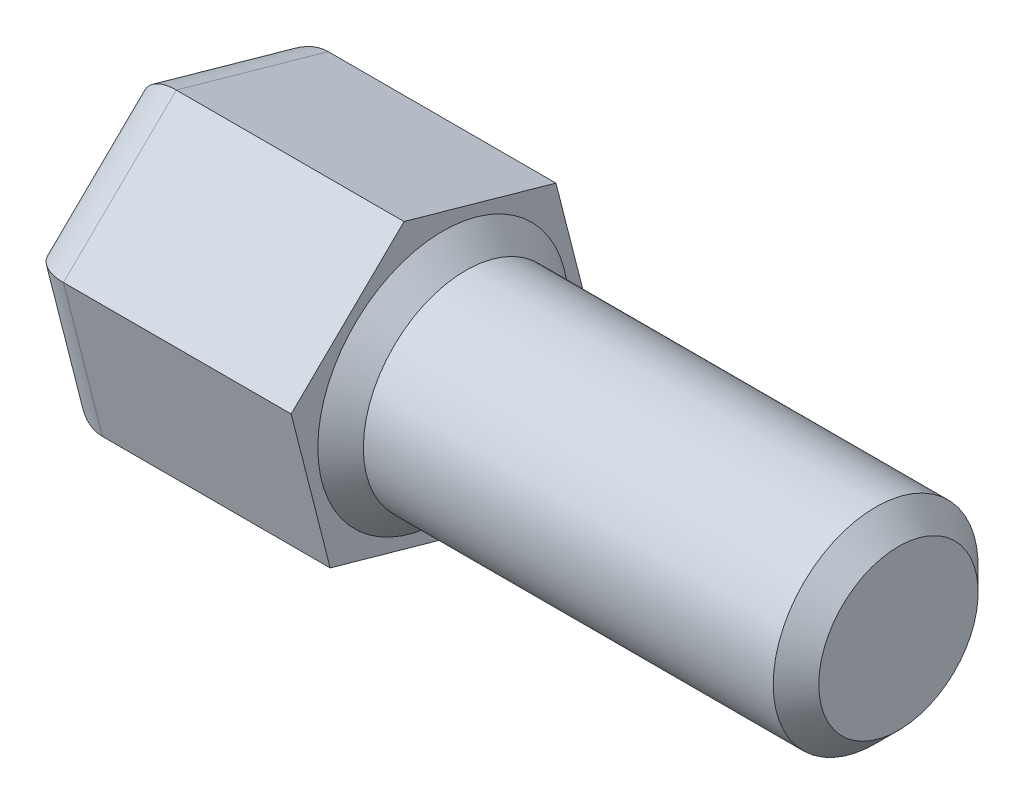
SolidWorks part; units mm, degrees
ref_plane "前基準面" through (0, 0, 0) normal (0, 0, 1) x (1, 0, 0)
ref_plane "上基準面" through (0, 0, 0) normal (0, 1, 0) x (1, 0, 0)
ref_plane "右基準面" through (0, 0, 0) normal (1, 0, 0) x (0, 0, -1)
sketch "草圖1" plane through (0, 0, 0) normal (0, 0, 1) x (1, 0, 0)
  line L1 (0, 0) -> (20, 0)
  line L2 (0, 0) -> (0, 4.5)
  line L3 (0, 4.5) -> (20, 4.5)
  line L4 (20, 0) -> (20, 4.5)
  dimension "D1" = 20
  dimension "D2" = 4.5
revolve "旋轉1" add sketch "草圖1" angle 360 about L1
sketch "草圖2" plane through (0, 0, 0) normal (-1, 0, 0) x (0, 0, 1)
  line L1 (1.7129, 6.7131) -> (-4.9573, 4.84)
  line L2 (-4.9573, 4.84) -> (-6.6702, -1.8731)
  line L3 (-6.6702, -1.8731) -> (-1.7129, -6.7131)
  line L4 (-1.7129, -6.7131) -> (4.9573, -4.84)
  line L5 (4.9573, -4.84) -> (6.6702, 1.8731)
  line L6 (6.6702, 1.8731) -> (1.7129, 6.7131)
  circle A0 centre (0, 0) radius 6 construction
  dimension "D1" = 12
extrude "填料-伸長1" add sketch "草圖2" along normal blind 12
fillet "圓角1" radius 2 6 edges at (-12, -4.2931, -4.1916) (-12, -5.7766, 1.6222) (-12, -1.4835, 5.8137) (-12, 4.2931, 4.1916) (-12, 1.4835, -5.8137) (-12, 5.7766, -1.6222)
chamfer "導角1" distance 1 angle 45 2 edges at (20, 0, 4.5) (0, 0, 4.5)
